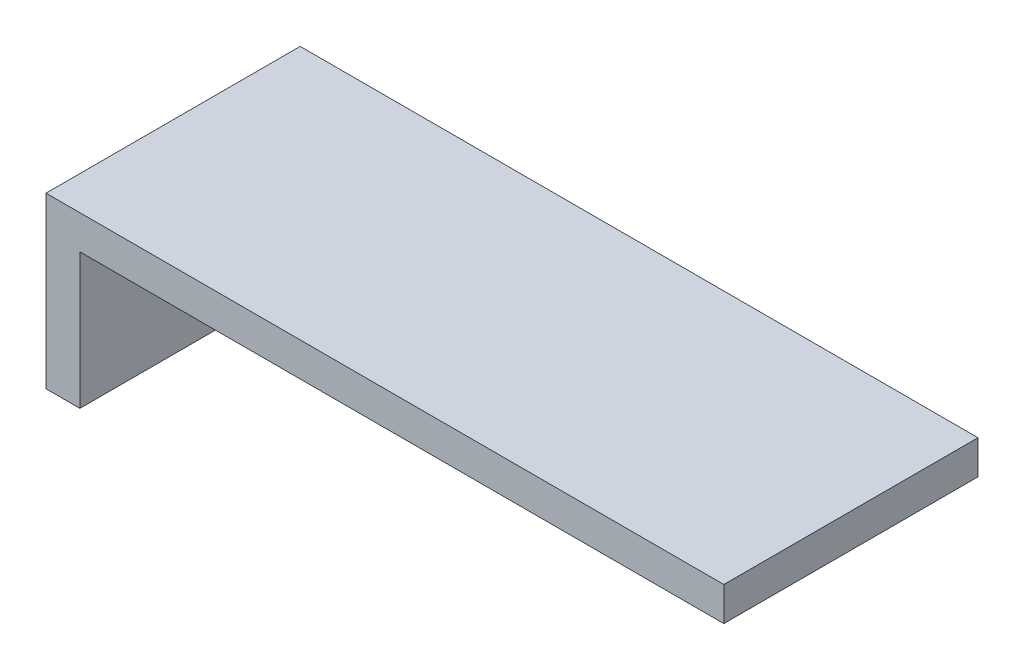
SolidWorks part; units mm, degrees
ref_plane "Front Plane" through (0, 0, 0) normal (0, 0, 1) x (1, 0, 0)
ref_plane "Top Plane" through (0, 0, 0) normal (0, 1, 0) x (1, 0, 0)
ref_plane "Right Plane" through (0, 0, 0) normal (1, 0, 0) x (0, 0, -1)
sketch "Sketch1" plane through (0, 0, 0) normal (0, 1, 0) x (1, 0, 0)
  line L1 (0, 0) -> (40, 0)
  line L2 (0, 0) -> (0, 15)
  line L3 (0, 15) -> (40, 15)
  line L4 (40, 0) -> (40, 15)
  dimension "D1" = 15
  dimension "D2" = 40
extrude "Boss-Extrude1" add sketch "Sketch1" along normal blind 2
sketch "Sketch2" plane through (0, 0, 0) normal (0, -1, 0) x (1, 0, 0)
  line L0 (40, -15) -> (0, -15) construction
  line L1 (0, 0) -> (2, 0)
  line L2 (0, 0) -> (0, -15)
  line L3 (0, -15) -> (2, -15)
  line L4 (2, 0) -> (2, -15)
  dimension "D1" = 2
extrude "Boss-Extrude2" add sketch "Sketch2" along normal blind 8
